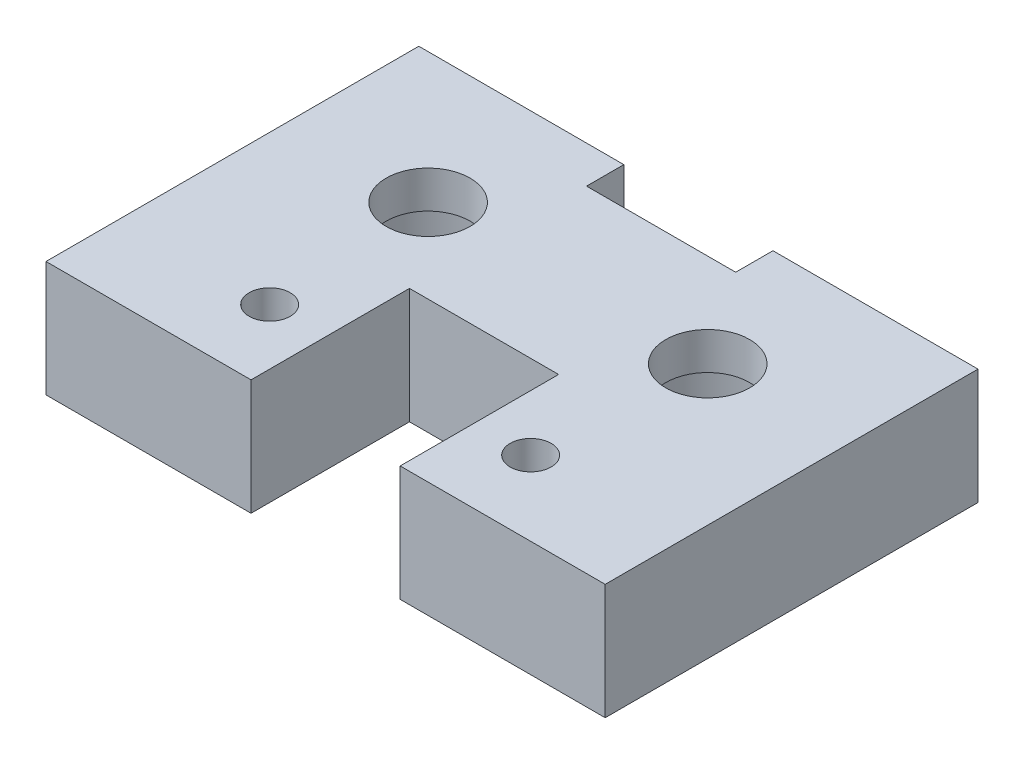
SolidWorks part; units mm, degrees
ref_plane "前视基准面" through (0, 0, 0) normal (0, 0, 1) x (1, 0, 0)
ref_plane "上视基准面" through (0, 0, 0) normal (0, 1, 0) x (1, 0, 0)
ref_plane "右视基准面" through (0, 0, 0) normal (1, 0, 0) x (0, 0, -1)
sketch "草图1" plane through (0, 0, 0) normal (0, 1, 0) x (1, 0, 0)
  line L1 (-15, -10) -> (15, -10)
  line L2 (-15, -10) -> (-15, 10)
  line L3 (-15, 10) -> (15, 10)
  line L4 (15, -10) -> (15, 10)
  line L5 (-15, -10) -> (15, 10) construction
  line L6 (-15, 10) -> (15, -10) construction
  point P0 (0, 0)
  dimension "D1" = 30
  dimension "D2" = 20
extrude "凸台-拉伸1" add sketch "草图1" along normal blind 4.2
sketch "草图2" plane through (0, 4.2, 0) normal (0, 1, 0) x (1, 0, 0)
  line L0 (0, 0) -> (0, 3) construction
  line L1 (-7.5, 3) -> (7.5, 3) construction
  line L2 (15, 10) -> (-15, 10) construction
  circle A0 centre (-7.5, 3) radius 4.15
  circle A1 centre (7.5, 3) radius 4.15
  point P7 (0, 3)
  point P8 (0, 0)
  point P10 (0, 0)
  dimension "D1" = 7
  dimension "D3" = 8.3
  dimension "D2" = 15
extrude "切除-拉伸1" cut sketch "草图2" against normal through all
sketch "草图3" plane through (0, 4.2, 0) normal (0, 1, 0) x (1, 0, 0)
  line L0 (0, 0) -> (0, -10) construction
  line L1 (-15, -10) -> (15, -10) construction
  line L2 (-7.5, 3) -> (7.5, 3) construction
  line L3 (-4, -1.5) -> (4, -1.5)
  line L4 (-4, -1.5) -> (-4, -10)
  line L5 (-4, -10) -> (4, -10)
  line L6 (4, -1.5) -> (4, -10)
  line L7 (-4, -1.5) -> (4, -10) construction
  line L8 (-4, -10) -> (4, -1.5) construction
  circle A0 centre (7.5, 3) radius 4.15 construction
  circle A1 centre (7.5, 3) radius 4.15 construction
  circle A2 centre (-7.5, 3) radius 4.15 construction
  circle A3 centre (-7.5, 3) radius 4.15 construction
  point P5 (0, -5.75)
  dimension "D1" = 4.5
  dimension "D2" = 8
extrude "切除-拉伸2" cut sketch "草图3" against normal through all
sketch "草图4" plane through (0, 4.2, 0) normal (0, 1, 0) x (1, 0, 0)
  line L8 (-4, -1.5) -> (4, -1.5)
  line L9 (4, -1.5) -> (4, -10)
  line L10 (4, -10) -> (15, -10)
  line L11 (15, -10) -> (15, 10)
  line L12 (15, 10) -> (-15, 10)
  line L13 (-15, 10) -> (-15, -10)
  line L14 (-15, -10) -> (-4, -10)
  line L15 (-4, -10) -> (-4, -1.5)
  line L16 (-4, -1.5) -> (4, -1.5)
  line L17 (4, -1.5) -> (4, -10)
  line L18 (4, -10) -> (15, -10)
  line L19 (15, -10) -> (15, 10)
  line L20 (15, 10) -> (-15, 10)
  line L21 (-15, 10) -> (-15, -10)
  line L22 (-15, -10) -> (-4, -10)
  line L23 (-4, -10) -> (-4, -1.5)
  dimension "D1" = 0
extrude "凸台-拉伸2" add sketch "草图4" along normal blind 2
sketch "草图5" plane through (0, 4.2, 0) normal (0, -1, 0) x (1, 0, 0)
  circle A0 centre (-7.5, -3) radius 2.25
  circle A1 centre (-7.5, -3) radius 4.15
  circle A2 centre (-7.5, -3) radius 4.15 construction
  circle A3 centre (7.5, -3) radius 4.15
  circle A4 centre (7.5, -3) radius 4.15 construction
  circle A5 centre (7.5, -3) radius 2.25
  dimension "D3" = 4.5
  dimension "D1" = 0
  dimension "D2" = 0
extrude "切除-拉伸3" cut sketch "草图5" against normal through all
sketch "草图6" plane through (0, 6.2, 0) normal (0, 1, 0) x (1, 0, 0)
  line L0 (0, 0) -> (0, 10) construction
  line L1 (15, 10) -> (-15, 10) construction
  line L3 (-4, 8) -> (4, 8)
  line L4 (-4, 8) -> (-4, 10)
  line L5 (-4, 10) -> (4, 10)
  line L6 (4, 8) -> (4, 10)
  line L7 (-4, 8) -> (4, 10) construction
  line L8 (-4, 10) -> (4, 8) construction
  point P5 (0, 9)
  point P10 (3.7538, 5.0227)
  dimension "D1" = 2
  dimension "D2" = 8
extrude "切除-拉伸4" cut sketch "草图6" against normal through all
sketch "草图7" plane through (0, 6.2, 0) normal (0, 1, 0) x (1, 0, 0)
  line L0 (-15, -10) -> (-4, -10) construction
  line L3 (-15, 10) -> (-15, -10) construction
  line L4 (0, 0) -> (0, -6.9878) construction
  circle A0 centre (-7, -6) radius 1.1
  circle A1 centre (7, -6) radius 1.1
  dimension "D3" = 2.2
  dimension "D1" = 4
  dimension "D2" = 8
extrude "切除-拉伸5" cut sketch "草图7" against normal through all
sketch "草图8" plane through (0, 0, 0) normal (0, -1, 0) x (1, 0, 0)
  line L0 (0, 0) -> (0, -5) construction
  line L2 (1.4, -3.6) -> (-1.4, -3.6)
  line L3 (1.4, -3.6) -> (1.4, -6.4)
  line L4 (1.4, -6.4) -> (-1.4, -6.4)
  line L5 (-1.4, -3.6) -> (-1.4, -6.4)
  line L6 (1.4, -3.6) -> (-1.4, -6.4) construction
  line L7 (1.4, -6.4) -> (-1.4, -3.6) construction
  line L8 (15, -10) -> (4, -10) construction
  dimension "D1" = 2.8
  dimension "D2" = 2.8
  dimension "D3" = 5
extrude "凸台-拉伸3" add sketch "草图8" along normal blind 3
